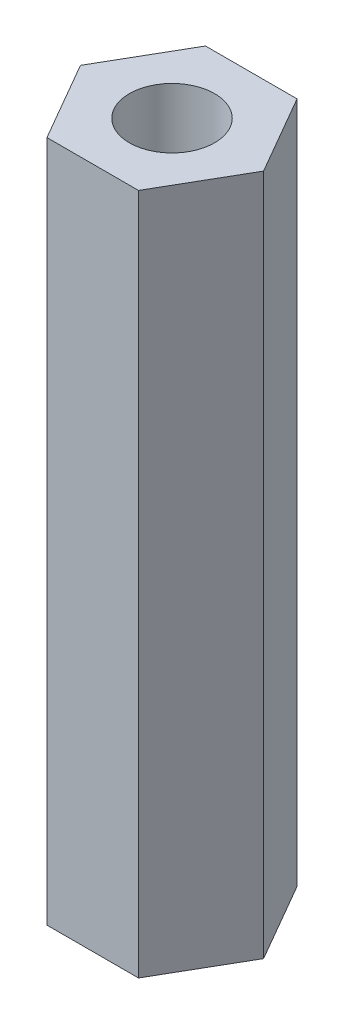
SolidWorks part; units mm, degrees
material "黄铜"
ref_plane "前视基准面" through (0, 0, 0) normal (0, 0, 1) x (1, 0, 0)
ref_plane "上视基准面" through (0, 0, 0) normal (0, 1, 0) x (1, 0, 0)
ref_plane "右视基准面" through (0, 0, 0) normal (1, 0, 0) x (0, 0, -1)
sketch "草图1" plane through (0, 0, 0) normal (0, 1, 0) x (1, 0, 0)
  line L1 (2.6847, 0) -> (1.3423, 2.325)
  line L2 (1.3423, 2.325) -> (-1.3423, 2.325)
  line L3 (-1.3423, 2.325) -> (-2.6847, 0)
  line L4 (-2.6847, 0) -> (-1.3423, -2.325)
  line L5 (-1.3423, -2.325) -> (1.3423, -2.325)
  line L6 (1.3423, -2.325) -> (2.6847, 0)
  circle A0 centre (0, 0) radius 2.325 construction
  dimension "D1" = 4.65
extrude "凸台-拉伸1" add sketch "草图1" along normal mid plane 20
hole_wizard "M3 螺纹孔1" positions "草图3" profile "草图2" tap size "M3" standard "GB"
sketch "草图3" plane through (0, -10, 0) normal (0, -1, 0) x (-1, 0, 0)
  point P0 (0, 0)
sketch "草图2" plane through (0, -10, 0) normal (1, 0, 0) x (0, 0, -1)
  line L0 (0, 0) -> (0, 8.2511)
  line L1 (0, 8.2511) -> (1.25, 7.5)
  line L2 (1.25, 7.5) -> (1.25, 0)
  line L5 (1.25, 0) -> (0, 0)
  line L10 (0, 8.2511) -> (-1.25, 7.5) construction
  line L11 (0, -6.35) -> (0, 107.95) construction
  dimension "螺纹孔钻头直径" = 2.5
  dimension "螺纹孔钻头深度" = 7.5
  dimension "导头角度" = 118
cosmetic thread "孔螺蚊线1" parameters "D1"=5, "D2"=3
mirror "镜向1" about plane through (0, 0, 0) normal (0, 1, 0) of "M3 螺纹孔1"
equation "\"高度\"= 5"
equation "\"对边距离\"= 4.65"
equation "\"D1@草图1\"=\"对边距离\""
equation "\"D1@凸台-拉伸1\"=\"高度\""
